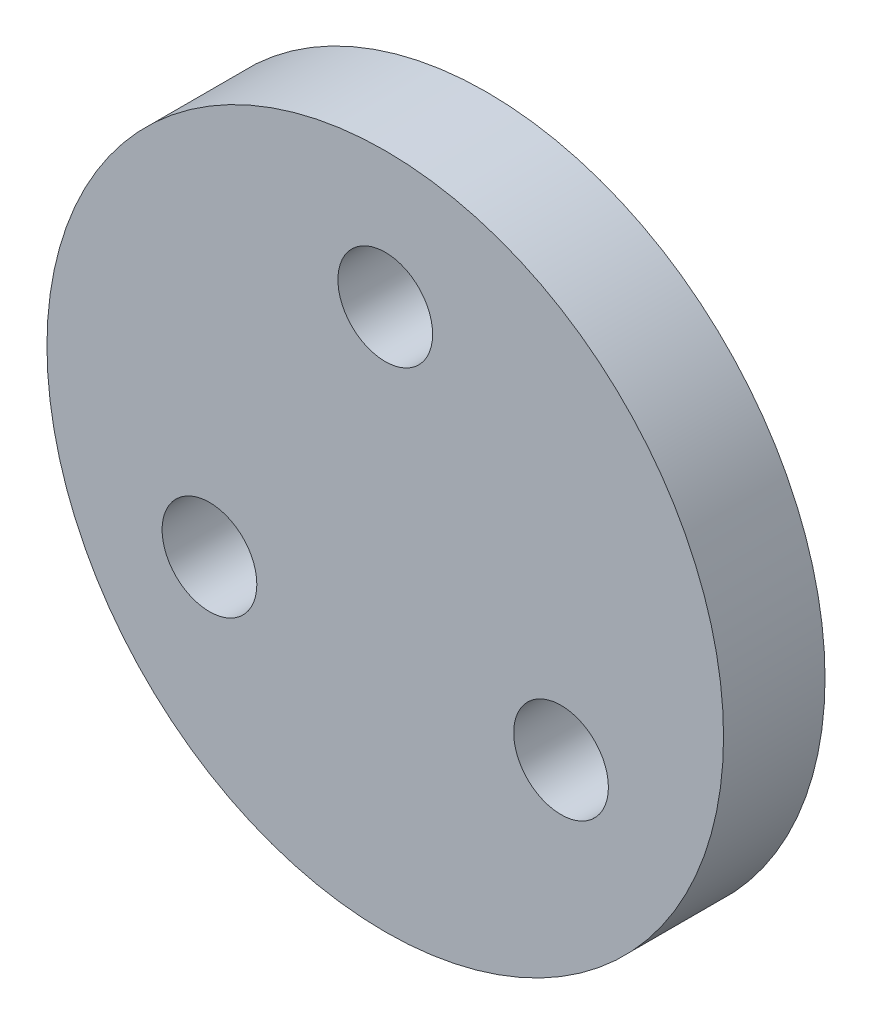
SolidWorks part; units mm, degrees
ref_plane "前视基准面" through (0, 0, 0) normal (0, 0, 1) x (1, 0, 0)
ref_plane "上视基准面" through (0, 0, 0) normal (0, 1, 0) x (1, 0, 0)
ref_plane "右视基准面" through (0, 0, 0) normal (1, 0, 0) x (0, 0, -1)
other "Configuration Table"
sketch "Sketch1" plane through (0, 0, 0) normal (0, 0, 1) x (1, 0, 0)
  circle A0 centre (0, 0) radius 3
  dimension "D1" = 6
extrude "Boss-Extrude1" add sketch "Sketch1" along normal blind 5
sketch "Sketch2" plane through (0, 0, 5) normal (0, 0, 1) x (1, 0, 0)
  circle A0 centre (0, 0) radius 10
  dimension "D1" = 20
extrude "Boss-Extrude2" add sketch "Sketch2" along normal blind 3
sketch "Sketch3" plane through (0, 0, 8) normal (0, 0, 1) x (1, 0, 0)
  circle A0 centre (0, 6) radius 1.4
  dimension "D1" = 2.8
  dimension "D2" = 6
extrude "Cut-Extrude1" cut sketch "Sketch3" against normal blind 3
pattern_circular "CirPattern1" count 3 over 360 about axis through (0, 0, 0) along (0, 0, 1) of "Cut-Extrude1"
chamfer "Chamfer1" distance 1 angle 45 1 edges at (3, 0, 0)
